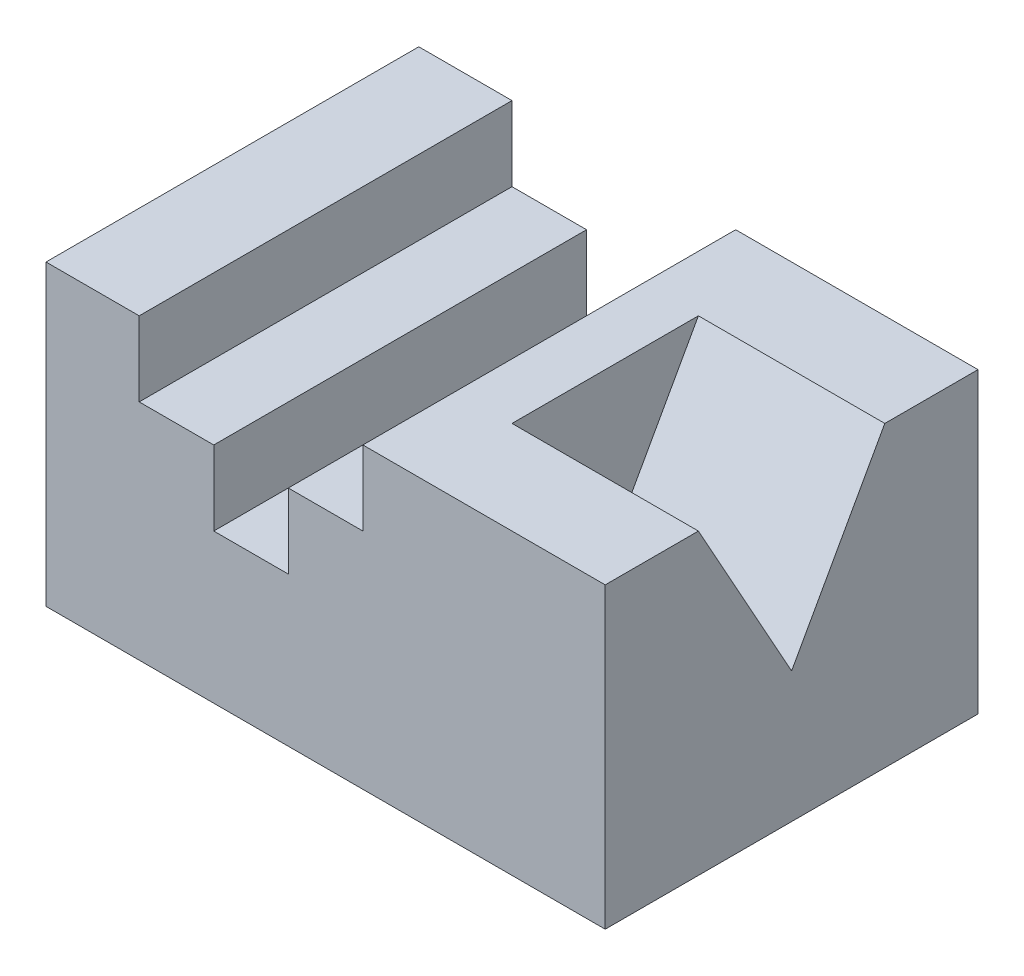
SolidWorks part; units mm, degrees
ref_plane "Front Plane" through (0, 0, 0) normal (0, 0, 1) x (1, 0, 0)
ref_plane "Top Plane" through (0, 0, 0) normal (0, 1, 0) x (1, 0, 0)
ref_plane "Right Plane" through (0, 0, 0) normal (1, 0, 0) x (0, 0, -1)
sketch "Sketch1" plane through (0, 0, 0) normal (0, 0, 1) x (1, 0, 0)
  line L0 (0, 0) -> (0, 80)
  line L1 (0, 80) -> (25, 80)
  line L2 (25, 80) -> (25, 60)
  line L3 (25, 60) -> (45, 60)
  line L4 (45, 60) -> (45, 40)
  line L5 (45, 40) -> (65, 40)
  line L6 (65, 40) -> (65, 60)
  line L7 (65, 60) -> (85, 60)
  line L8 (85, 60) -> (85, 80)
  line L9 (85, 80) -> (150, 80)
  line L10 (150, 80) -> (150, 0)
  line L11 (150, 0) -> (0, 0)
  dimension "D1" = 150
  dimension "D2" = 80
  dimension "D3" = 25
  dimension "D4" = 20
  dimension "D5" = 20
extrude "Boss-Extrude1" add sketch "Sketch1" along normal mid plane 100
sketch "Sketch2" plane through (0, 0, 0) normal (1, 0, 0) x (0, 0, -1)
  line L0 (-25, 80) -> (25, 80)
  line L1 (-50, 80) -> (50, 80) construction
  line L2 (25, 80) -> (0, 35)
  line L3 (0, 35) -> (-25, 80)
  line L4 (50, 0) -> (50, 80) construction
  point P4 (0, 80)
  point P6 (0, 0)
  point P8 (0, 38.913)
  point P9 (21.1973, 80)
  dimension "D1" = 45
  dimension "D2" = 25
extrude "Cut-Extrude1" cut sketch "Sketch2" against normal blind 50 from surface at 150 starting at face at (150, 40, 0)
